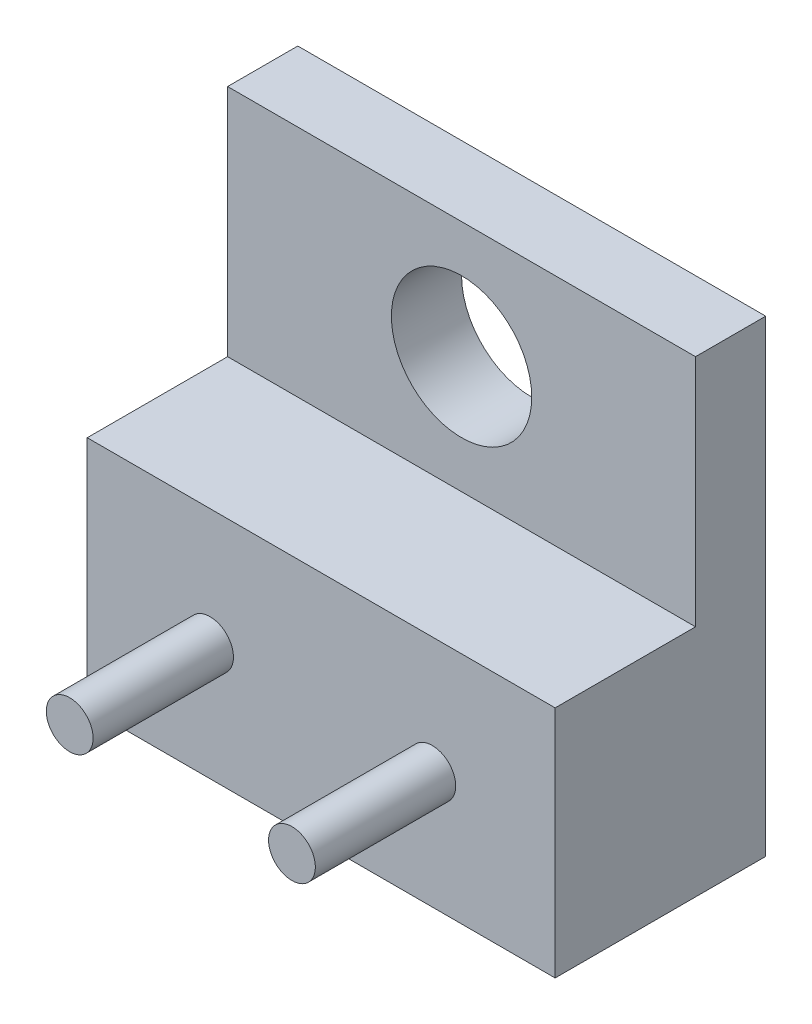
SolidWorks part; units mm, degrees
ref_plane "前视基准面" through (0, 0, 0) normal (0, 0, 1) x (1, 0, 0)
ref_plane "上视基准面" through (0, 0, 0) normal (0, 1, 0) x (1, 0, 0)
ref_plane "右视基准面" through (0, 0, 0) normal (1, 0, 0) x (0, 0, -1)
sketch "草图1" plane through (0, 0, 0) normal (0, 0, 1) x (1, 0, 0)
  line L1 (0, 0) -> (20, 0)
  line L2 (0, 0) -> (0, 20)
  line L3 (0, 20) -> (20, 20)
  line L4 (20, 0) -> (20, 20)
  dimension "D1" = 20
  dimension "D2" = 20
extrude "凸台-拉伸1" add sketch "草图1" along normal blind 9
sketch "草图2" plane through (0, 0, 9) normal (0, 0, 1) x (1, 0, 0)
  line L0 (0, 20) -> (0, 0) construction
  line L4 (0, 0) -> (20, 0) construction
  circle A0 centre (5.25, 5) radius 1
  circle A1 centre (14.75, 4.9811) radius 1
  dimension "D1" = 2
  dimension "D2" = 9.5
  dimension "D3" = 5.25
  dimension "D4" = 5
extrude "凸台-拉伸2" add sketch "草图2" along normal blind 6
sketch "草图3" plane through (0, 0, 9) normal (0, 0, 1) x (1, 0, 0)
  line L0 (20, 0) -> (20, 20) construction
  line L2 (0, 20) -> (20, 20)
  line L3 (0, 20) -> (0, 10)
  line L4 (0, 10) -> (20, 10)
  line L5 (20, 20) -> (20, 10)
  dimension "D1" = 10
extrude "切除-拉伸1" cut sketch "草图3" against normal blind 6
sketch "草图4" plane through (0, 0, 3) normal (0, 0, 1) x (1, 0, 0)
  line L0 (0, 15) -> (20, 15) construction
  line L1 (0, 20) -> (0, 10) construction
  line L2 (20, 10) -> (20, 20) construction
  circle A0 centre (10, 15) radius 3
  dimension "D1" = 6
extrude "切除-拉伸2" cut sketch "草图4" against normal up to next
